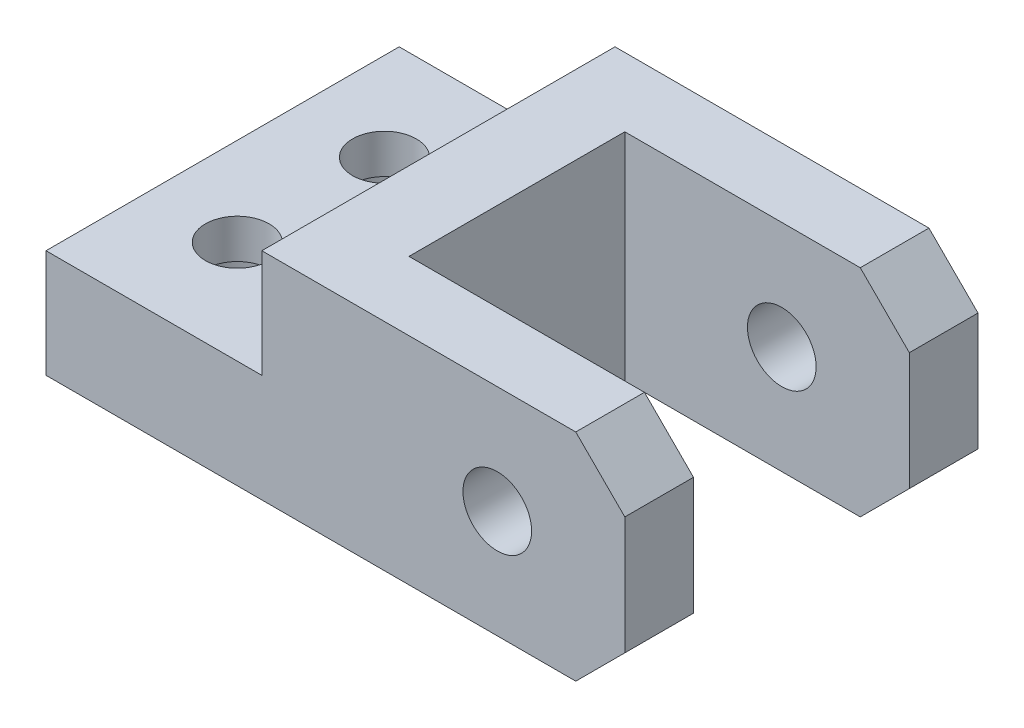
SolidWorks part; units mm, degrees
ref_plane "Face" through (0, 0, 0) normal (0, 0, 1) x (1, 0, 0)
ref_plane "Dessus" through (0, 0, 0) normal (0, 1, 0) x (1, 0, 0)
ref_plane "Droite" through (0, 0, 0) normal (1, 0, 0) x (0, 0, -1)
sketch "Esquisse1" plane through (0, 0, 0) normal (0, 0, 1) x (1, 0, 0)
  line L0 (0, 0) -> (0, 11)
  line L1 (0, 11) -> (32, 11)
  line L2 (37, 6) -> (37, -6)
  line L3 (32, -11) -> (-22, -11)
  line L4 (-22, -11) -> (-22, 0)
  line L5 (-22, 0) -> (0, 0)
  line L6 (32, 11) -> (37, 6)
  line L7 (37, -6) -> (32, -11)
  circle A0 centre (24, 0) radius 3.5
  point P3 (37, 11)
  point P4 (37, -11)
  dimension "D5" = 7
  dimension "D1" = 22
  dimension "D2" = 11
  dimension "D3" = 22
  dimension "D4" = 24
  dimension "D7" = 5
  dimension "D8" = 5
  dimension "D6" = 13
extrude "Base-Extrusion" add sketch "Esquisse1" against normal up to vertex (36 mm away)
hole_wizard "Chambrage pour vis à tête cylindrique à 6 pans creux (vis CHC) M51" positions "Esquisse3" profile "Esquisse2" counterbore size "M5" standard "ISO" end condition through all
sketch "Esquisse3" plane through (0, -11, 0) normal (0, -1, 0) x (1, 0, 0)
  point P0 (-13, -25.5)
  point P1 (-13, -10.5)
sketch "Esquisse2" plane through (-13, -11, -25.5) normal (1, 0, 0) x (0, 0, -1)
  line L0 (0, 0) -> (0, 22)
  line L1 (0, 22) -> (3.25, 22)
  line L3 (3.25, 22) -> (3.25, 7)
  line L4 (3.25, 7) -> (6, 7)
  line L5 (6, 7) -> (6, 0)
  line L7 (6, 0) -> (0, 0)
  line L11 (0, -6.35) -> (0, 107.95) construction
  dimension "Diamètre du perçage jusqu'au prochain" = 6.5
  dimension "Profondeur du perçage jusqu'au prochain" = 22
  dimension "Diamètre du chambrage" = 12
  dimension "Profondeur du chambrage" = 7
sketch "Esquisse4" plane through (37, 0, 0) normal (1, 0, 0) x (0, 0, -1)
  line L1 (18, 11) -> (18, -14.047) construction
  line L4 (29, -12.9733) -> (18, -12.9733)
  line L5 (7, -12.9733) -> (18, -12.9733)
  line L6 (7, -12.9733) -> (7, 12.0267)
  line L7 (7, 12.0267) -> (18, 12.0267)
  line L8 (29, -12.9733) -> (29, 12.0267)
  line L9 (29, 12.0267) -> (18, 12.0267)
  line L10 (36, 11) -> (0, 11) construction
  dimension "D1" = 22
extrude "Enlèv. mat.-Extru.1" cut sketch "Esquisse4" against normal blind 29
